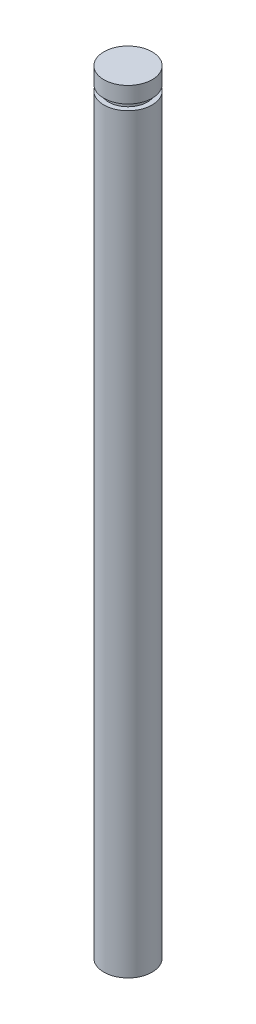
SolidWorks part; units mm, degrees
ref_plane "Front Plane" through (0, 0, 0) normal (0, 0, 1) x (1, 0, 0)
ref_plane "Top Plane" through (0, 0, 0) normal (0, 1, 0) x (1, 0, 0)
ref_plane "Right Plane" through (0, 0, 0) normal (1, 0, 0) x (0, 0, -1)
sketch "Sketch1" plane through (0, 0, 0) normal (0, 1, 0) x (1, 0, 0)
  circle A0 centre (0, 0) radius 18.75
  dimension "D1" = 37.5
extrude "Boss-Extrude1" add sketch "Sketch1" along normal blind 12.5 contours A0
sketch "Sketch2" plane through (0, 0, 0) normal (0, -1, 0) x (1, 0, 0)
  circle A0 centre (0, 0) radius 15
  dimension "D1" = 30
extrude "Boss-Extrude2" add sketch "Sketch2" along normal blind 4.5
sketch "Sketch3" plane through (0, -4.5, 0) normal (0, -1, 0) x (1, 0, 0)
  circle A0 centre (0, 0) radius 18.75
extrude "Boss-Extrude3" add sketch "Sketch3" along normal blind 583
